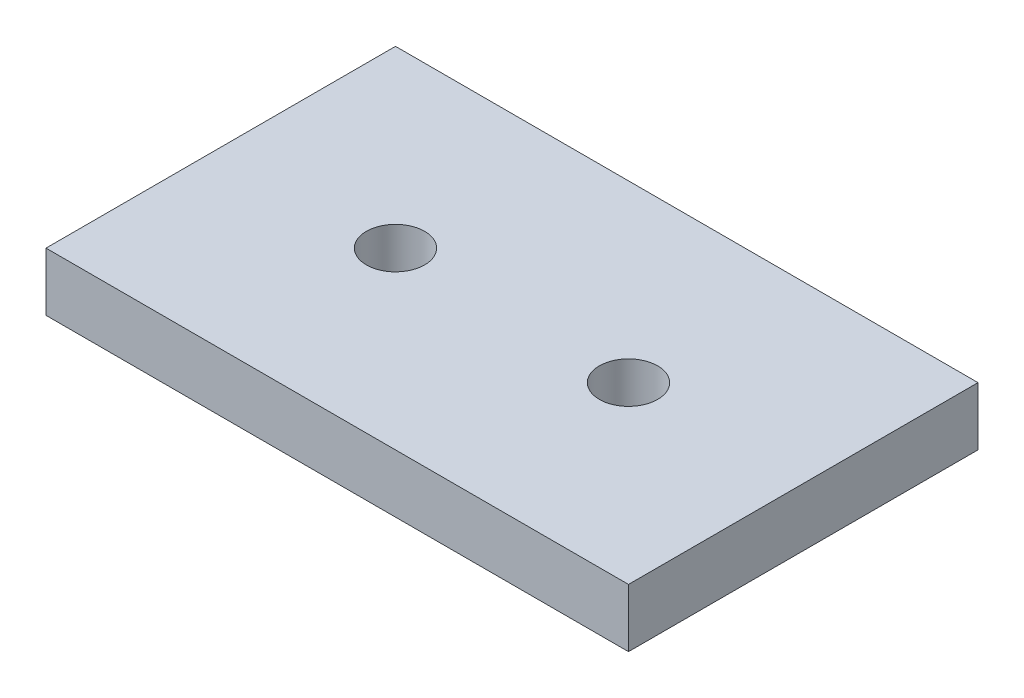
SolidWorks part; units mm, degrees
ref_plane "前视基准面" through (0, 0, 0) normal (0, 0, 1) x (1, 0, 0)
ref_plane "上视基准面" through (0, 0, 0) normal (0, 1, 0) x (1, 0, 0)
ref_plane "右视基准面" through (0, 0, 0) normal (1, 0, 0) x (0, 0, -1)
other "Configuration Table"
sketch "草图1" plane through (0, 0, 0) normal (0, 1, 0) x (1, 0, 0)
  line L1 (-50, -30) -> (50, -30)
  line L2 (-50, -30) -> (-50, 30)
  line L3 (-50, 30) -> (50, 30)
  line L4 (50, -30) -> (50, 30)
  line L5 (-50, -30) -> (50, 30) construction
  line L6 (-50, 30) -> (50, -30) construction
extrude "凸台-拉伸1" add sketch "草图1" along normal blind 10
sketch "草图2" plane through (0, 0, 0) normal (0, 1, 0) x (1, 0, 0)
  circle A0 centre (-20, 0) radius 5
extrude "切除-拉伸1" cut sketch "草图2" along normal blind 20
sketch "草图3" plane through (0, 0, 0) normal (0, 1, 0) x (1, 0, 0)
  circle A0 centre (20, 0) radius 5
extrude "切除-拉伸2" cut sketch "草图3" along normal blind 20
chamfer "倒角1" distance 1 angle 45 2 edges at (20, 0, 5) (-20, 0, 5)
sketch "草图4" plane through (0, 0, 0) normal (0, 1, 0) x (1, 0, 0)
  line L0 (-10, -20) -> (10, -20)
